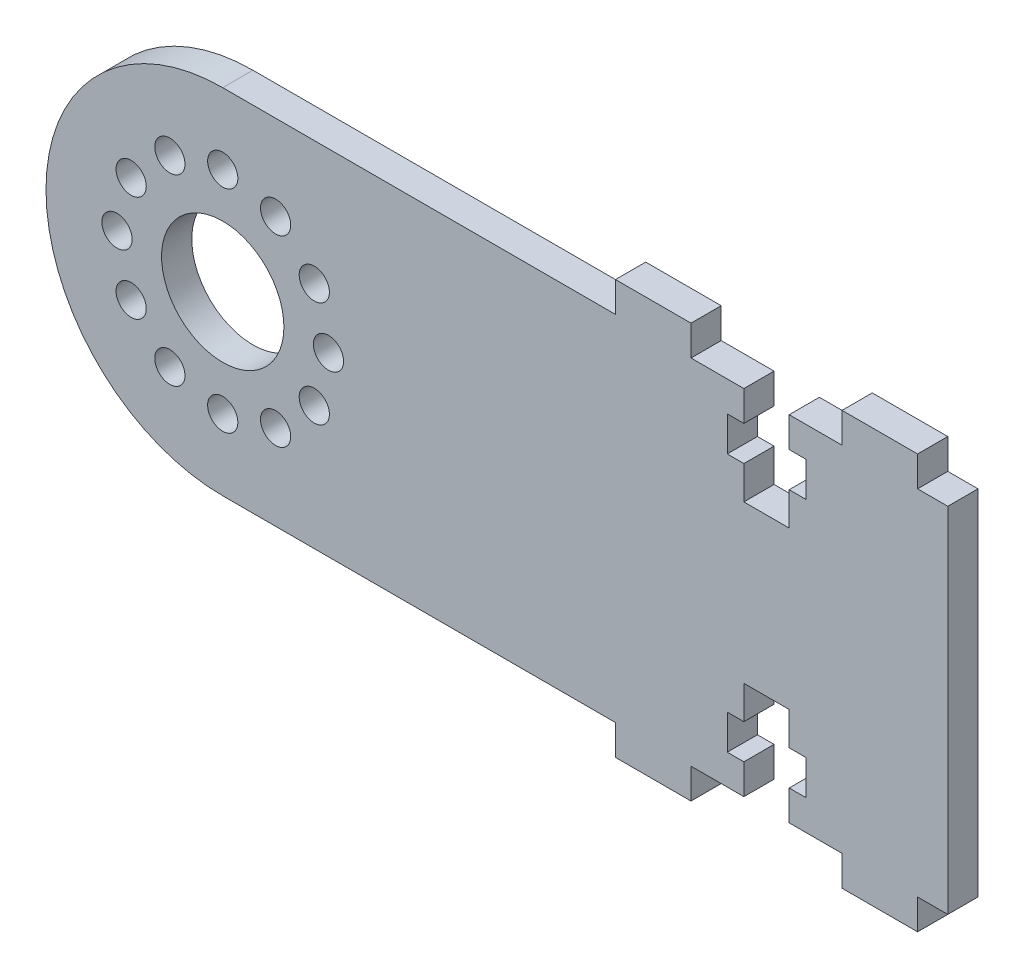
SolidWorks part; units mm, degrees
ref_plane "Front Plane" through (0, 0, 0) normal (0, 0, 1) x (1, 0, 0)
ref_plane "Top Plane" through (0, 0, 0) normal (0, 1, 0) x (1, 0, 0)
ref_plane "Right Plane" through (0, 0, 0) normal (1, 0, 0) x (0, 0, -1)
sketch "Sketch1" plane through (0, 0, 0) normal (0, 0, 1) x (1, 0, 0)
  line L0 (0, 11.7) -> (48, 11.7) construction
  line L1 (48, 11.7) -> (48, -11.7)
  line L2 (48, -11.7) -> (0, -11.7) construction
  line L3 (0, 0) -> (48, 0) construction
  line L4 (0, 11.7) -> (26, 11.7)
  line L5 (46, 11.7) -> (48, 11.7)
  line L6 (48, -11.7) -> (46, -11.7)
  line L7 (26, -11.7) -> (0, -11.7)
  arc A13 (0, 11.7) -> (0, -11.7) centre (0, 0) ccw
  line B0 (0, 0) -> (7, 0) construction
  circle B1 centre (0, 0) radius 4.05
  circle B2 centre (7, 0) radius 1
  circle B3 centre (6.0622, -3.5) radius 1
  circle B4 centre (3.5, -6.0622) radius 1
  circle B5 centre (0, -7) radius 1
  circle B6 centre (-3.5, -6.0622) radius 1
  circle B7 centre (-6.0622, -3.5) radius 1
  circle B8 centre (-7, 0) radius 1
  circle B9 centre (-6.0622, 3.5) radius 1
  circle B10 centre (-3.5, 6.0622) radius 1
  circle B11 centre (0, 7) radius 1
  circle B12 centre (3.5, 6.0622) radius 1
  circle B13 centre (6.0622, 3.5) radius 1
  line B14 (36, -11.7) -> (36, -5.2) construction
  line B15 (34.5, -11.7) -> (31, -11.7)
  line B16 (31, -13.7) -> (26, -13.7)
  line B17 (26, -13.7) -> (26, -11.7)
  line B18 (31, -13.7) -> (31, -11.7)
  line B19 (37.5, -11.7) -> (41, -11.7)
  line B20 (41, -11.7) -> (41, -13.7)
  line B21 (41, -13.7) -> (46, -13.7)
  line B22 (46, -13.7) -> (46, -11.7)
  line B23 (34.5, -11.7) -> (37.5, -11.7) construction
  line B24 (37.5, -11.7) -> (37.5, -9.7)
  line B25 (37.5, -7.4) -> (38.6, -7.4)
  line B26 (33.4, -9.7) -> (33.4, -7.4)
  line B27 (38.6, -9.7) -> (37.5, -9.7)
  line B28 (37.5, -7.4) -> (37.5, -5.2)
  line B29 (37.5, -5.2) -> (34.5, -5.2)
  line B30 (34.5, -5.2) -> (34.5, -7.4)
  line B31 (34.5, -9.7) -> (33.4, -9.7)
  line B32 (38.6, -7.4) -> (38.6, -9.7)
  line B33 (33.4, -7.4) -> (34.5, -7.4)
  line B34 (34.5, -9.7) -> (34.5, -11.7)
  line B35 (36, -5.2) -> (36, -11.7) construction
  line B36 (36, 11.7) -> (36, 5.2) construction
  line B37 (34.5, 11.7) -> (31, 11.7)
  line B38 (31, 13.7) -> (26, 13.7)
  line B39 (26, 13.7) -> (26, 11.7)
  line B40 (31, 13.7) -> (31, 11.7)
  line B41 (37.5, 11.7) -> (41, 11.7)
  line B42 (41, 11.7) -> (41, 13.7)
  line B43 (41, 13.7) -> (46, 13.7)
  line B44 (46, 13.7) -> (46, 11.7)
  line B45 (34.5, 11.7) -> (37.5, 11.7) construction
  line B46 (37.5, 11.7) -> (37.5, 9.7)
  line B47 (37.5, 7.4) -> (38.6, 7.4)
  line B48 (33.4, 9.7) -> (33.4, 7.4)
  line B49 (38.6, 9.7) -> (37.5, 9.7)
  line B50 (37.5, 7.4) -> (37.5, 5.2)
  line B51 (37.5, 5.2) -> (34.5, 5.2)
  line B52 (34.5, 5.2) -> (34.5, 7.4)
  line B53 (34.5, 9.7) -> (33.4, 9.7)
  line B54 (38.6, 7.4) -> (38.6, 9.7)
  line B55 (33.4, 7.4) -> (34.5, 7.4)
  line B56 (34.5, 9.7) -> (34.5, 11.7)
  line B57 (36, 5.2) -> (36, 11.7) construction
  dimension "D1" = 23.4
  dimension "D2" = 36
  dimension "D3" = 12
sketch_block_instance "Block1-1"
sketch_block "Block1" parameters "D2"=2, "D3"=8.1, "D1"=7
sketch_block_instance "Block2-1"
sketch_block "Block2" parameters "D1"=10, "D2"=5, "D3"=2, "D4"=5.2, "D5"=3, "D6"=2.3, "D7"=2, "D8"=6.5
sketch_block_instance "Block2-2"
extrude "Boss-Extrude1" add sketch "Sketch1" along normal blind 2 contours B53 B56 B37 B40 B38 B39 L4 A13 L7 B17 B16 B18 B15 B34 B31 B26 B33 B30 B29 B28 B25 B32 B27 B24 B19 B20 B21 B22 L6 L1 L5 B44 B43 B42 B41 B46 B49 B54 B47 B50 B51 B52 B55 B48 B1 B2 B3
